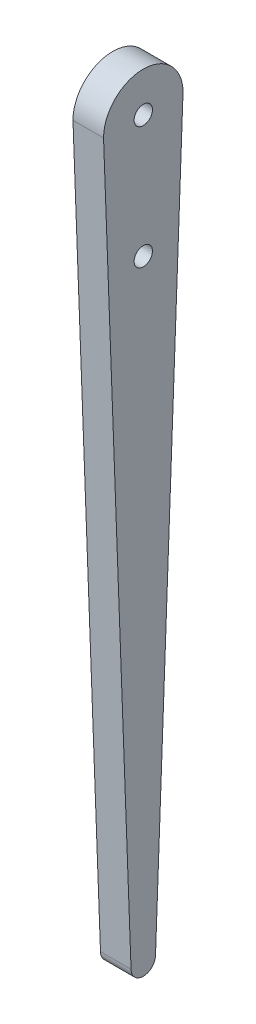
SolidWorks part; units mm, degrees
ref_plane "Front" through (0, 0, 0) normal (0, 0, 1) x (1, 0, 0)
ref_plane "Top" through (0, 0, 0) normal (0, 1, 0) x (1, 0, 0)
ref_plane "Right" through (0, 0, 0) normal (1, 0, 0) x (0, 0, -1)
sketch "Sketch1" plane through (0, 0, 0) normal (1, 0, 0) x (0, 0, -1)
  line L0 (0, 60) -> (0, -60) construction
  line L1 (-6.5, 60) -> (-2, -60)
  line L2 (6.5, 60) -> (2, -60)
  circle A0 centre (0, 60) radius 1.5
  arc A1 (-6.5, 60) -> (6.5, 60) centre (0, 60) cw
  arc A2 (2, -60) -> (-2, -60) centre (0, -60) cw
  circle A3 centre (0, 40) radius 1.5
  point P3 (0, 0)
  dimension "D3" = 5
  dimension "D4" = 3
  dimension "D5" = 2
  dimension "D1" = 20
  dimension "D2" = 120
extrude "Boss-Extrude1" add sketch "Sketch1" along normal blind 5
